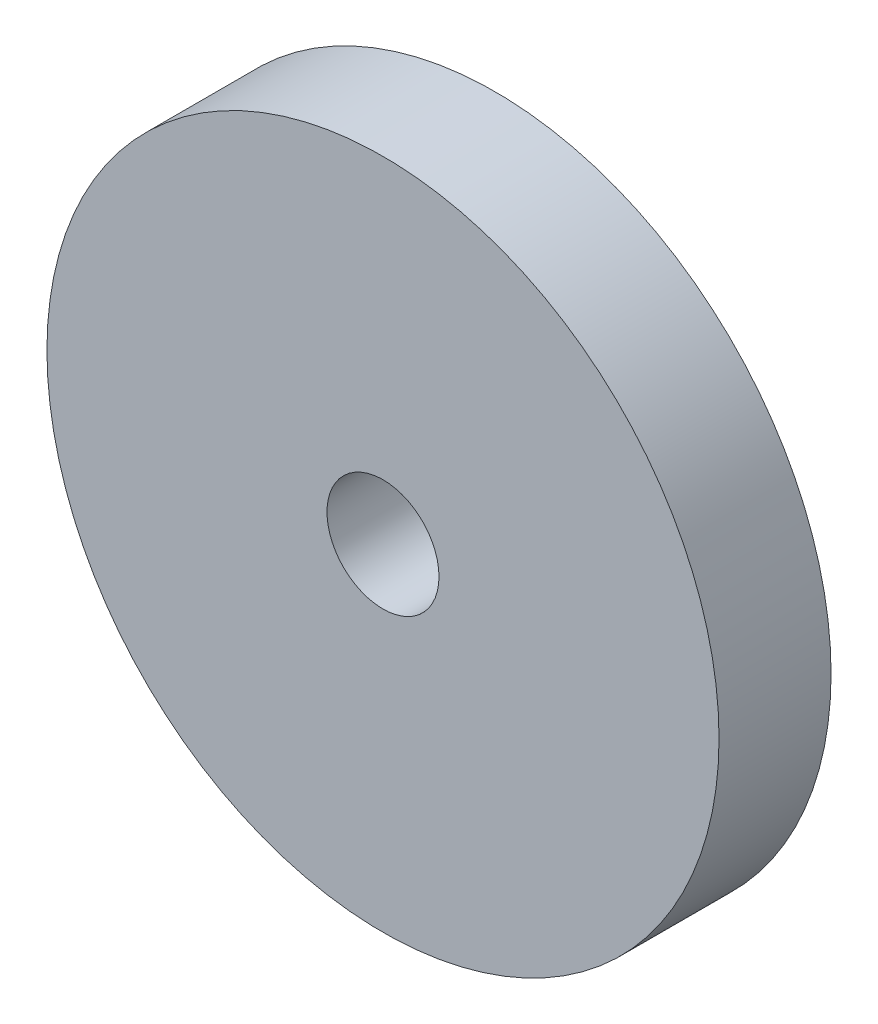
SolidWorks part; units mm, degrees
ref_plane "Alzado" through (0, 0, 0) normal (0, 0, 1) x (1, 0, 0)
ref_plane "Planta" through (0, 0, 0) normal (0, 1, 0) x (1, 0, 0)
ref_plane "Vista lateral" through (0, 0, 0) normal (1, 0, 0) x (0, 0, -1)
sketch "Model" plane through (0, 0, 0) normal (0, 0, 1) x (1, 0, 0)
  circle A0 centre (18.5643, 286.9748) radius 1.5
  circle A1 centre (18.5643, 286.9748) radius 9
extrude "Saliente-Extruir1" add sketch "Model" along normal blind 3
